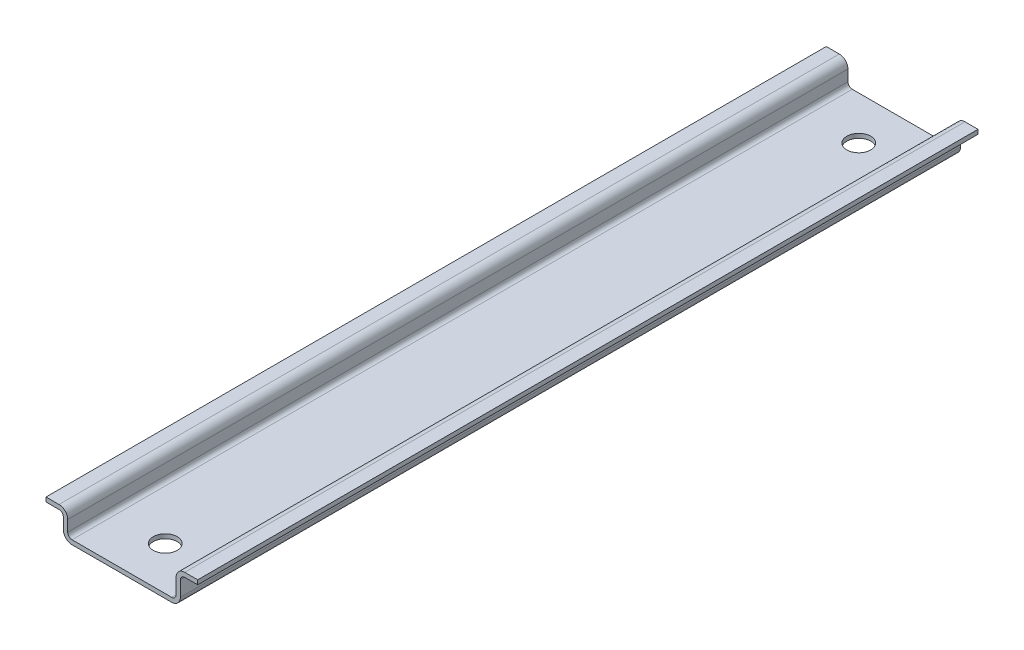
SolidWorks part; units mm, degrees
ref_plane "Front Plane" through (0, 0, 0) normal (0, 0, 1) x (1, 0, 0)
ref_plane "Top Plane" through (0, 0, 0) normal (0, 1, 0) x (1, 0, 0)
ref_plane "Right Plane" through (0, 0, 0) normal (1, 0, 0) x (0, 0, -1)
sketch "Sketch1" plane through (0, 0, 0) normal (0, 0, 1) x (1, 0, 0)
  line L0 (2, 0) -> (25, 0)
  line L1 (0, 2) -> (0, 4.5445)
  line L2 (-1, 5.5445) -> (-4, 5.5445)
  line L3 (27, 2) -> (27, 5.5)
  line L4 (28, 6.5) -> (31, 6.5)
  line L5 (-1, 6.5445) -> (-4, 6.5445)
  line L6 (1, 2) -> (1, 4.5445)
  line L7 (2, 1) -> (25, 1)
  line L8 (26, 2) -> (26, 5.5)
  line L9 (28, 7.5) -> (31, 7.5)
  line L10 (-4, 5.5445) -> (-4, 6.5445)
  line L11 (31, 6.5) -> (31, 7.5)
  line L12 (27, 0) -> (27, 6.5) construction
  line L13 (27, 6.5) -> (31, 6.5) construction
  line L14 (1, 1) -> (26, 1) construction
  line L15 (26, 1) -> (26, 7.5) construction
  line L16 (1, 1) -> (1, 6.5445) construction
  line L17 (0, 0) -> (0, 5.5445) construction
  line L18 (0, 5.5445) -> (-4, 5.5445) construction
  line L19 (26, 7.5) -> (31, 7.5) construction
  line L20 (0, 0) -> (27, 0) construction
  line L21 (1, 6.5445) -> (-4, 6.5445) construction
  arc A0 (27, 5.5) -> (28, 6.5) centre (28, 5.5) cw
  arc A1 (25, 1) -> (26, 2) centre (25, 2) ccw
  arc A2 (1, 2) -> (2, 1) centre (2, 2) ccw
  arc A3 (0, 4.5445) -> (-1, 5.5445) centre (-1, 4.5445) ccw
  arc A4 (26, 5.5) -> (28, 7.5) centre (28, 5.5) cw
  arc A5 (25, 0) -> (27, 2) centre (25, 2) ccw
  arc A6 (2, 0) -> (0, 2) centre (2, 2) cw
  arc A7 (-1, 6.5445) -> (1, 4.5445) centre (-1, 4.5445) cw
  point P16 (27, 6.5)
  point P26 (0, 5.5445)
  dimension "D7" = 1
  dimension "D8" = 2
  dimension "D2" = 4
  dimension "D3" = 4
  dimension "D5" = 7.5
  dimension "D6" = 35
  dimension "D4" = 1
extrude "Boss-Extrude1" add sketch "Sketch1" along normal blind 180
sketch "Sketch2" plane through (0, 1, 0) normal (0, 1, 0) x (1, 0, 0)
  line L0 (25, -180) -> (2, -180) construction
  line L1 (25, 0) -> (2, 0) construction
  line L3 (2, -180) -> (2, 0) construction
  circle A0 centre (13.5, -10) radius 2.75
  circle A1 centre (13.5, -170) radius 2.75
  dimension "D2" = 10
  dimension "D3" = 5.5
  dimension "D4" = 5.5
  dimension "D1" = 10
  dimension "D5" = 11.5
  dimension "D6" = 11.5
extrude "Cut-Extrude1" cut sketch "Sketch2" against normal blind 1
